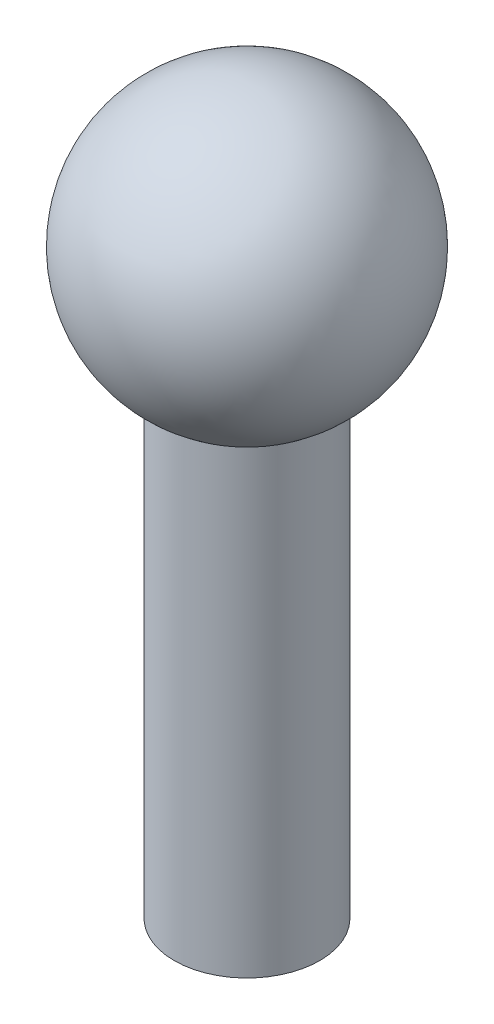
SolidWorks part; units mm, degrees
ref_plane "Front Plane" through (0, 0, 0) normal (0, 0, 1) x (1, 0, 0)
ref_plane "Top Plane" through (0, 0, 0) normal (0, 1, 0) x (1, 0, 0)
ref_plane "Right Plane" through (0, 0, 0) normal (1, 0, 0) x (0, 0, -1)
sketch "Sketch2" plane through (0, 0, 0) normal (0, 0, 1) x (1, 0, 0)
  line L0 (0, 0) -> (0, 16) construction
  line L1 (0, 0) -> (-2, 0)
  line L2 (-2, 0) -> (-2, 12.6519)
  line L3 (0, 19.9) -> (0, 0)
  circle A0 centre (0, 16) radius 3.9
  dimension "D3" = 7.8
  dimension "D1" = 16
  dimension "D2" = 2
revolve "Revolve1" add sketch "Sketch2" angle 360 about L3
